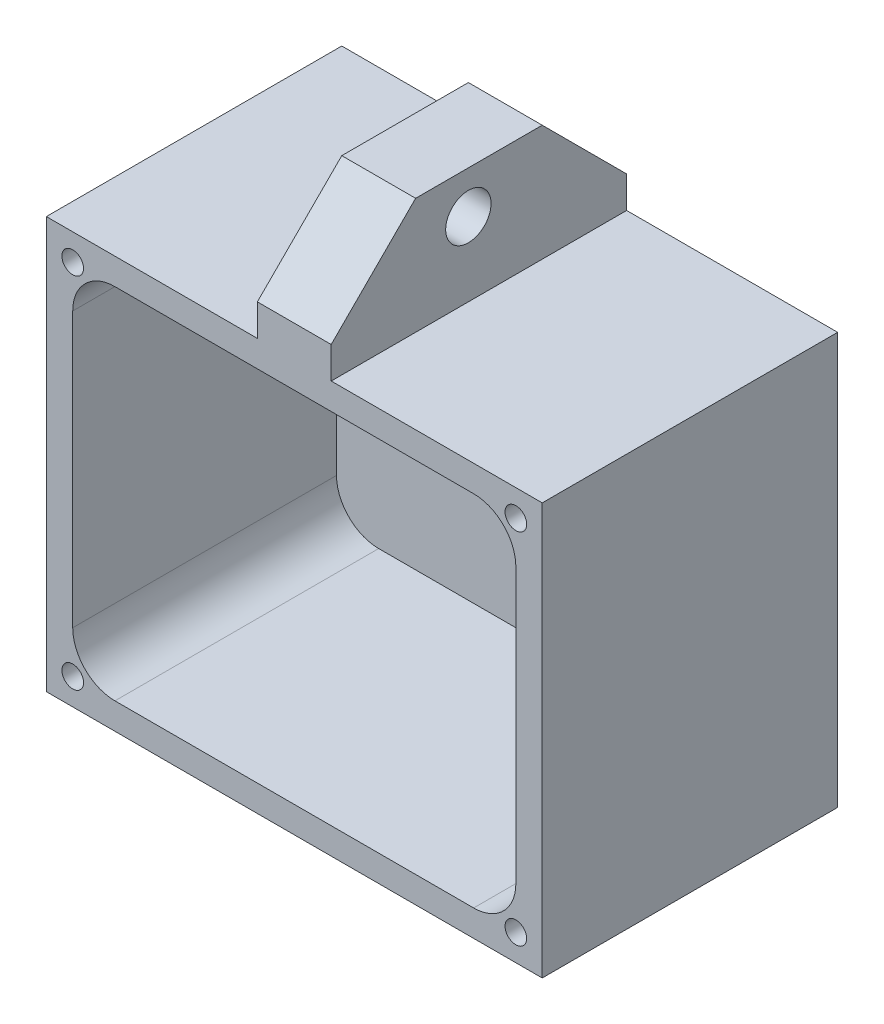
SolidWorks part; units mm, degrees
ref_plane "前视基准面" through (0, 0, 0) normal (0, 0, 1) x (1, 0, 0)
ref_plane "上视基准面" through (0, 0, 0) normal (0, 1, 0) x (1, 0, 0)
ref_plane "右视基准面" through (0, 0, 0) normal (1, 0, 0) x (0, 0, -1)
sketch "草图1" plane through (0, 0, 0) normal (0, 0, 1) x (1, 0, 0)
  line L1 (-23.5, -19.5) -> (23.5, -19.5)
  line L2 (-23.5, -19.5) -> (-23.5, 19.5)
  line L3 (-23.5, 19.5) -> (23.5, 19.5)
  line L4 (23.5, -19.5) -> (23.5, 19.5)
  line L5 (-23.5, -19.5) -> (23.5, 19.5) construction
  line L6 (-23.5, 19.5) -> (23.5, -19.5) construction
  point P0 (0, 0)
  dimension "D1" = 47
  dimension "D2" = 39
extrude "凸台-拉伸1" add sketch "草图1" along normal blind 28
sketch "草图4" plane through (0, 0, 28) normal (0, 0, 1) x (1, 0, 0)
  line L1 (-21, 17) -> (21, 17)
  line L2 (-21, 17) -> (-21, -17)
  line L3 (-21, -17) -> (21, -17)
  line L4 (21, 17) -> (21, -17)
  line L5 (-21, 17) -> (21, -17) construction
  line L6 (-21, -17) -> (21, 17) construction
  point P0 (0, 0)
  dimension "D1" = 42
  dimension "D2" = 34
extrude "切除-拉伸1" cut sketch "草图4" against normal offset from surface (25 mm away) 3 up to face at (0, 0, 0)
fillet "圆角1" radius 4 4 edges at (21, -17, 15.5) (-21, -17, 15.5) (-21, 17, 15.5) (21, 17, 15.5)
hole_wizard "M2.5 螺纹孔1" positions "草图6" profile "草图5" tap size "M2.5" standard "GB"
sketch "草图6" plane through (0, 0, 28) normal (0, 0, 1) x (1, 0, 0)
  line L1 (-21, -17) -> (21, -17)
  line L2 (-21, -17) -> (-21, 17)
  line L3 (-21, 17) -> (21, 17)
  line L4 (21, -17) -> (21, 17)
  line L5 (-21, -17) -> (21, 17) construction
  line L6 (-21, 17) -> (21, -17) construction
  line L7 (0, 0) -> (21, 0) construction
  line L9 (0, 0) -> (0, 17) construction
  point P2 (21, 17)
  point P5 (-21, -17)
  point P6 (-21, 17)
  point P7 (21, -17)
  dimension "D1" = 42
  dimension "D2" = 34
sketch "草图5" plane through (21, 17, 28) normal (1, 0, 0) x (0, -1, 0)
  line L0 (0, 0) -> (0, 6.9659)
  line L1 (0, 6.9659) -> (1.025, 6.35)
  line L2 (1.025, 6.35) -> (1.025, 0)
  line L5 (1.025, 0) -> (0, 0)
  line L10 (0, 6.9659) -> (-1.025, 6.35) construction
  line L11 (0, -6.35) -> (0, 107.95) construction
  dimension "螺纹孔钻头直径" = 2.05
  dimension "螺纹孔钻头深度" = 6.35
  dimension "导头角度" = 118
cosmetic thread "孔螺蚊线1" parameters "D1"=5, "D2"=2.5
cosmetic thread "孔螺蚊线2" parameters "D1"=5, "D2"=2.5
cosmetic thread "孔螺蚊线3" parameters "D1"=5, "D2"=2.5
cosmetic thread "孔螺蚊线4" parameters "D1"=5, "D2"=2.5
hole_wizard "M3 螺纹孔1" positions "草图8" profile "草图9" tap size "M3" standard "GB" end condition up to next
sketch "草图8" plane through (0, 0, 0) normal (0, 0, -1) x (-1, 0, 0)
  line L0 (0, 0) -> (0, 13.3443) construction
  line L1 (23.5, -19.5) -> (-23.5, -19.5) construction
  point P0 (-12, -6.5)
  point P2 (12, -6.5)
  point P10 (0, 10.5)
  dimension "D1" = 24
  dimension "D2" = 17
  dimension "D3" = 13
sketch "草图9" plane through (12, -6.5, 0) normal (1, 0, 0) x (0, 1, 0)
  line L0 (0, 0) -> (0, 3)
  line L1 (0, 3) -> (1.25, 3)
  line L2 (1.25, 3) -> (1.25, 0)
  line L5 (1.25, 0) -> (0, 0)
  line L11 (0, -6.35) -> (0, 107.95) construction
  dimension "通孔螺纹孔钻头直径" = 2.5
  dimension "通孔螺纹孔钻头深度" = 3
cosmetic thread "孔螺蚊线5" parameters "D2"=3
cosmetic thread "孔螺蚊线6" parameters "D2"=3
cosmetic thread "孔螺蚊线7" parameters "D2"=3
sketch "草图10" plane through (0, 0, 3) normal (0, 0, 1) x (1, 0, 0)
  circle A0 centre (0, 0) radius 6
  dimension "D2" = 12
extrude "切除-拉伸2" cut sketch "草图10" against normal up to next
sketch "草图11" plane through (0, 0, 0) normal (0, 0, -1) x (-1, 0, 0)
  line L0 (-23.5, 19.5) -> (23.5, 19.5) construction
  line L1 (-3.5, 30.5) -> (3.5, 30.5)
  line L2 (-3.5, 30.5) -> (-3.5, 19.5)
  line L3 (-3.5, 19.5) -> (3.5, 19.5)
  line L4 (3.5, 30.5) -> (3.5, 19.5)
  line L5 (-3.5, 30.5) -> (3.5, 19.5) construction
  line L6 (-3.5, 19.5) -> (3.5, 30.5) construction
  point P0 (0, 25)
  dimension "D1" = 7
  dimension "D2" = 11
extrude "凸台-拉伸2" add sketch "草图11" against normal up to surface (28 mm away) up to face at (22.025, 17, 28)
hole_wizard "M4 间隙孔1" positions "草图13" profile "草图12" hole size "M4" standard "GB" end condition up to next
sketch "草图13" plane through (3.5, 0, 0) normal (1, 0, 0) x (0, 0, -1)
  line L0 (-28, 19.5) -> (0, 19.5) construction
  line L1 (-28, 19.5) -> (-28, 30.5) construction
  point P0 (-15, 26.5)
  dimension "D1" = 7
  dimension "D2" = 13
sketch "草图12" plane through (3.5, 26.5, 15) normal (0, 1, 0) x (0, 0, -1)
  line L0 (0, 0) -> (0, 7)
  line L1 (0, 7) -> (2.15, 7)
  line L2 (2.15, 7) -> (2.15, 0)
  line L5 (2.15, 0) -> (0, 0)
  line L11 (0, -6.35) -> (0, 107.95) construction
  dimension "通孔孔直径" = 4.3
  dimension "通孔孔深度" = 7
chamfer "倒角1" distance 8 angle 45 2 edges at (0, 30.5, 28) (0, 30.5, 0)
